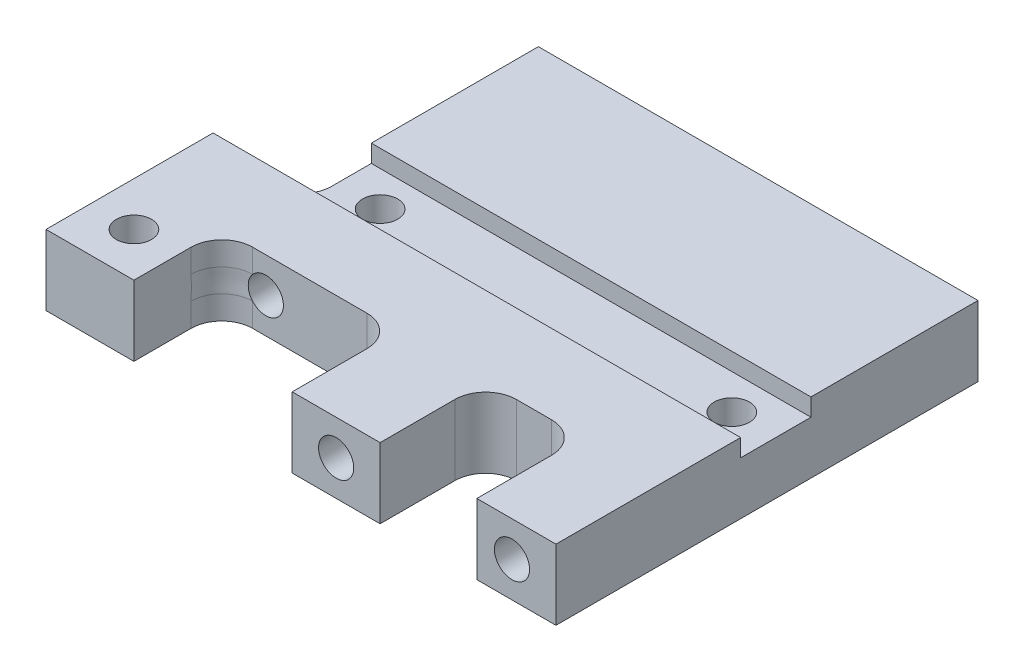
SolidWorks part; units mm, degrees
material "PVC rigide"
ref_plane "Plan de face" through (0, 0, 0) normal (0, 0, 1) x (1, 0, 0)
ref_plane "Plan de dessus" through (0, 0, 0) normal (0, 1, 0) x (1, 0, 0)
ref_plane "Plan de droite" through (0, 0, 0) normal (1, 0, 0) x (0, 0, -1)
sketch "Esquisse1" plane through (0, 0, 0) normal (0, 1, 0) x (1, 0, 0)
  line L1 (-57.1481, 46.0417) -> (-7.1481, 46.0417)
  line L2 (-57.1481, 46.0417) -> (-57.1481, 10.0417)
  line L4 (-7.1481, 46.0417) -> (-7.1481, 16.0417)
  line L5 (-48.1481, 10.0417) -> (-37.1481, 10.0417)
  line L6 (-16.1481, 10.0417) -> (-16.1481, -1.9583)
  line L7 (-16.1481, -1.9583) -> (-7.1481, -1.9583)
  line L8 (-7.1481, -1.9583) -> (-7.1481, 16.0417)
  line L9 (-27.1481, 10.0417) -> (-16.1481, 10.0417)
  line L10 (-48.1481, 10.0417) -> (-57.1481, 10.0417)
  line L11 (-37.1481, 10.0417) -> (-37.1481, -1.9583)
  line L12 (-37.1481, -1.9583) -> (-27.1481, -1.9583)
  line L13 (-27.1481, 10.0417) -> (-27.1481, -1.9583)
  dimension "D4" = 20
  dimension "D1" = 50
  dimension "D2" = 12
  dimension "D5" = 9
  dimension "D6" = 20
extrude "Boss.-Extru.1" add sketch "Esquisse1" along normal blind 8
sketch "Esquisse2" plane through (0, 0, 1.9583) normal (0, 0, 1) x (1, 0, 0)
  line L2 (-7.1481, 8) -> (-7.1481, 0) construction
  circle A0 centre (-52.1481, 4) radius 2
  circle A1 centre (-12.1481, 4) radius 2
  circle A2 centre (-32.1481, 4) radius 2
  point P15 (-12.1481, 4)
  dimension "D1" = 4
  dimension "D3" = 5
extrude "Enlèv. mat.-Extru.1" cut sketch "Esquisse2" against normal blind 15
sketch "Esquisse3" plane through (0, 0, -46.0417) normal (0, 0, -1) x (-1, 0, 0)
  line L0 (7.1481, 4) -> (57.1481, 4) construction
  line L1 (7.1481, 8) -> (7.1481, 0) construction
  line L2 (57.1481, 8) -> (57.1481, 0) construction
  circle A0 centre (12.1481, 4) radius 2
  circle A1 centre (52.1481, 4) radius 2
  dimension "D1" = 4
  dimension "D2" = 5
  dimension "D3" = 5
extrude "Enlèv. mat.-Extru.2" cut sketch "Esquisse3" against normal blind 10
sketch "Esquisse4" plane through (0, 8, 0) normal (0, 1, 0) x (1, 0, 0)
  line L0 (-62.8741, 23.0417) -> (2.0024, 23.0417) construction
  line L1 (-7.1481, 46.0417) -> (-57.1481, 46.0417) construction
  line L2 (-57.1481, 46.0417) -> (-57.1481, 10.0417) construction
  line L3 (-7.1481, -1.9583) -> (-7.1481, 46.0417) construction
  circle A0 centre (-52.1481, 23.0417) radius 2
  circle A1 centre (-12.1481, 23.0417) radius 2
  dimension "D2" = 4
  dimension "D1" = 23
  dimension "D3" = 5
  dimension "D4" = 5
extrude "Enlèv. mat.-Extru.3" cut sketch "Esquisse4" against normal blind 10
chamfer "Chanfrein1" distance 2.5 angle 45 2 edges at (-52.1481, 0, -25.0417) (-12.1481, 0, -25.0417)
sketch "Esquisse5" plane through (0, 8, 0) normal (0, 1, 0) x (1, 0, 0)
  line L0 (-57.1481, 46.0417) -> (-57.1481, 10.0417) construction
  line L1 (-57.1481, 27.0417) -> (-7.1481, 27.0417)
  line L2 (-57.1481, 27.0417) -> (-57.1481, 19.0417)
  line L3 (-57.1481, 19.0417) -> (-7.1481, 19.0417)
  line L4 (-7.1481, 27.0417) -> (-7.1481, 19.0417)
  line L5 (-7.1481, -1.9583) -> (-7.1481, 46.0417) construction
  circle A0 centre (-52.1481, 23.0417) radius 2 construction
  dimension "D1" = 4
  dimension "D2" = 8
extrude "Enlèv. mat.-Extru.4" cut sketch "Esquisse5" against normal blind 2
sketch "Esquisse6" plane through (-57.1481, 0, 0) normal (-1, 0, 0) x (0, 0, 1)
  line L0 (-46.0417, 0) -> (-10.0417, 0) construction
  line L1 (-19.0417, 8) -> (-0.0417, 8)
  line L2 (-19.0417, 8) -> (-19.0417, 0)
  line L3 (-19.0417, 0) -> (-0.0417, 0)
  line L4 (-0.0417, 8) -> (-0.0417, 0)
  line L6 (1.9583, 8) -> (1.9583, 0) construction
  dimension "D1" = 2
extrude "Boss.-Extru.2" add sketch "Esquisse6" along normal blind 10
fillet "Congé1" radius 3.5 5 edges at (-16.1481, 4, -10.0417) (-27.1481, 4, -10.0417) (-37.1481, 4, -10.0417) (-57.1481, 3, -19.0417) (-57.1481, 4, -10.0417)
sketch "Esquisse7" plane through (0, 8, 0) normal (0, 1, 0) x (1, 0, 0)
  line L0 (-67.1481, 0.0417) -> (-67.1481, 19.0417) construction
  line L1 (-67.1481, 0.0417) -> (-57.1481, 0.0417) construction
  circle A0 centre (-62.1481, 5.0417) radius 2
  dimension "D3" = 4
  dimension "D1" = 5
  dimension "D2" = 5
extrude "Enlèv. mat.-Extru.5" cut sketch "Esquisse7" against normal through all
